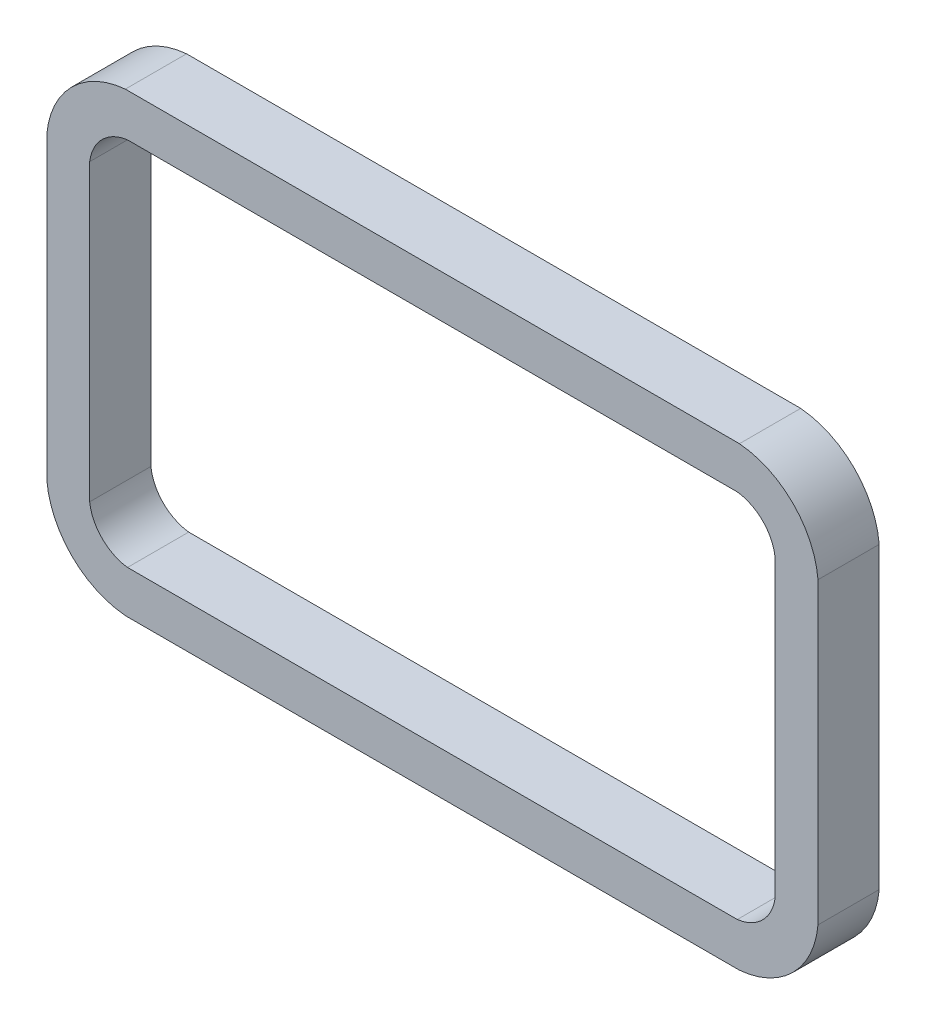
SolidWorks part; units mm, degrees
ref_plane "Спереди" through (0, 0, 0) normal (0, 0, 1) x (1, 0, 0)
ref_plane "Сверху" through (0, 0, 0) normal (0, 1, 0) x (1, 0, 0)
ref_plane "Справа" through (0, 0, 0) normal (1, 0, 0) x (0, 0, -1)
sketch "Эскиз1" plane through (0, 0, 0) normal (0, 0, 1) x (1, 0, 0)
  line L0 (-48.9505, 23.2005) -> (48.9505, -23.2005) construction
  line L1 (-48.9505, -23.2005) -> (0, 0) construction
  line L11 (63, -24.4198) -> (63, 24.4198)
  line L12 (50.1698, 37.25) -> (-50.1698, 37.25)
  line L13 (-63, 24.4198) -> (-63, -24.4198)
  line L14 (-50.1698, -37.25) -> (50.1698, -37.25)
  line L18 (0, 0) -> (48.9505, 23.2005) construction
  line L19 (56, -24.065) -> (56, 24.065)
  line L20 (49.815, 30.25) -> (-49.815, 30.25)
  line L21 (-56, 24.065) -> (-56, -24.065)
  line L22 (-49.815, -30.25) -> (49.815, -30.25)
  arc A4 (-50.1698, 37.25) -> (-63, 24.4198) centre (-48.9505, 23.2005) ccw
  arc A5 (50.1698, 37.25) -> (63, 24.4198) centre (48.9505, 23.2005) cw
  arc A6 (50.1698, -37.25) -> (63, -24.4198) centre (48.9505, -23.2005) ccw
  arc A7 (-50.1698, -37.25) -> (-63, -24.4198) centre (-48.9505, -23.2005) cw
  arc A8 (49.815, 30.25) -> (56, 24.065) centre (48.9505, 23.2005) cw
  arc A9 (-49.815, 30.25) -> (-56, 24.065) centre (-48.9505, 23.2005) ccw
  arc A10 (-49.815, -30.25) -> (-56, -24.065) centre (-48.9505, -23.2005) cw
  arc A11 (49.815, -30.25) -> (56, -24.065) centre (48.9505, -23.2005) ccw
  point P3 (0, 0)
  point P14 (-2.9058, -1.4232)
  dimension "D1" = 7
extrude "Бобышка-Вытянуть1" add sketch "Эскиз1" along normal blind 10
